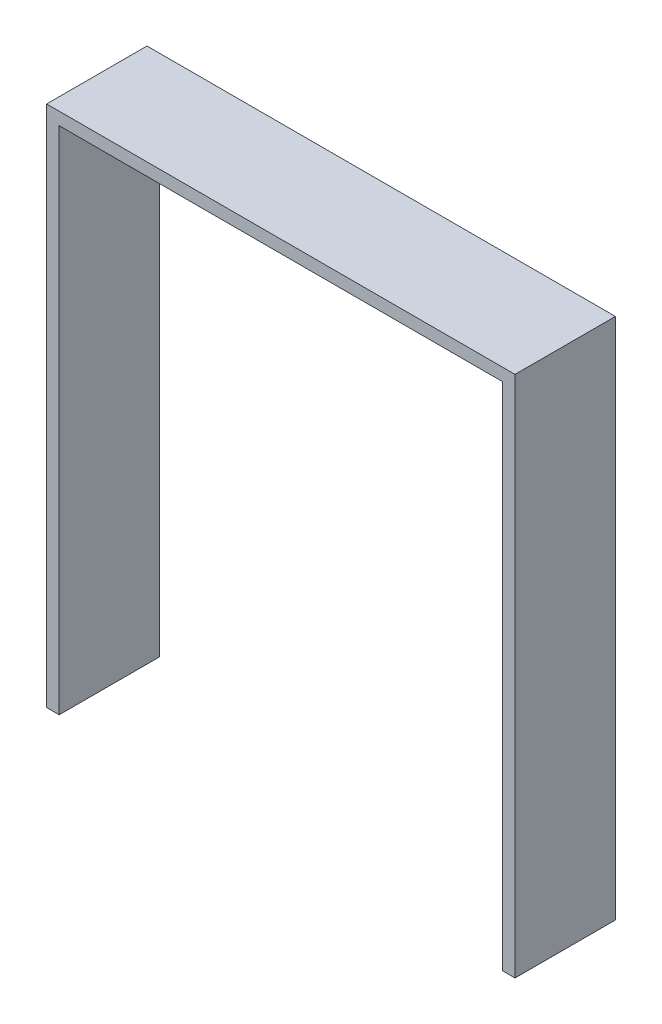
SolidWorks part; units mm, degrees
ref_plane "前视基准面" through (0, 0, 0) normal (0, 0, 1) x (1, 0, 0)
ref_plane "上视基准面" through (0, 0, 0) normal (0, 1, 0) x (1, 0, 0)
ref_plane "右视基准面" through (0, 0, 0) normal (1, 0, 0) x (0, 0, -1)
other "Configuration Table"
sketch "草图1" plane through (0, 0, 0) normal (0, 0, 1) x (1, 0, 0)
  line L0 (-3, 0) -> (-3, 125)
  line L1 (-3, 125) -> (109, 125)
  line L2 (109, 125) -> (109, 0)
  line L3 (109, 0) -> (106, 0)
  line L4 (106, 0) -> (106, 122)
  line L5 (106, 122) -> (0, 122)
  line L6 (0, 122) -> (0, 0)
  line L7 (0, 0) -> (-3, 0)
  dimension "x0" = 3
  dimension "x2" = 109
  dimension "x4" = 106
  dimension "y1" = 125
  dimension "y5" = 122
extrude "Extrude" add sketch "草图1" along normal blind 24
